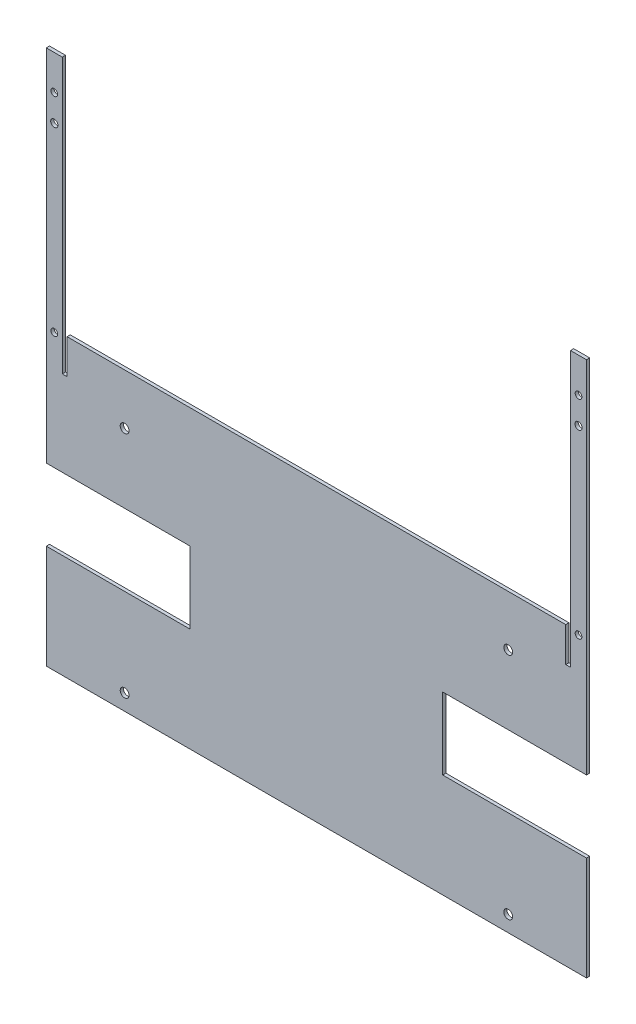
SolidWorks part; units mm, degrees
ref_plane "Plan de face" through (0, 0, 0) normal (0, 0, 1) x (1, 0, 0)
ref_plane "Plan de dessus" through (0, 0, 0) normal (0, 1, 0) x (1, 0, 0)
ref_plane "Plan de droite" through (0, 0, 0) normal (1, 0, 0) x (0, 0, -1)
sketch "Esquisse1" plane through (0, 0, 0) normal (0, 0, 1) x (1, 0, 0)
  line L1 (-169, -167.5) -> (169, -167.5)
  line L2 (-169, -167.5) -> (-169, 167.5)
  line L3 (-169, 167.5) -> (169, 167.5)
  line L4 (169, -167.5) -> (169, 167.5)
  line L5 (-169, -167.5) -> (169, 167.5) construction
  line L6 (-169, 167.5) -> (169, -167.5) construction
  point P0 (0, 0)
  dimension "D1" = 338
  dimension "D2" = 335
extrude "Boss.-Extru.1" add sketch "Esquisse1" along normal blind 2
sketch "Esquisse2" plane through (0, 0, 2) normal (0, 0, 1) x (1, 0, 0)
  line L0 (0, 0) -> (0, 137.1014) construction
  line L1 (169, 167.5) -> (-169, 167.5) construction
  line L2 (-159, 167.5) -> (159, 167.5)
  line L4 (-159, 17.5) -> (159, 17.5)
  line L5 (159, 167.5) -> (159, 17.5)
  line L6 (169, -167.5) -> (169, 167.5) construction
  line L7 (169, -102.5) -> (79, -102.5)
  line L8 (169, -102.5) -> (169, -57.5)
  line L9 (169, -57.5) -> (79, -57.5)
  line L10 (79, -102.5) -> (79, -57.5)
  line L12 (-79, -102.5) -> (-79, -57.5)
  line L13 (-169, -57.5) -> (-79, -57.5)
  line L14 (-169, -102.5) -> (-169, -57.5)
  line L15 (-169, -102.5) -> (-79, -102.5)
  line L16 (-159, 167.5) -> (-159, 17.5)
  point P6 (0, 167.5)
  point P23 (0, 17.5)
  dimension "D1" = 10
  dimension "D2" = 150
  dimension "D3" = 45
  dimension "D4" = 90
  dimension "D5" = 57.5
extrude "Enlèv. mat.-Extru.1" cut sketch "Esquisse2" against normal through all
hole_wizard "Dégagement M41" positions "Esquisse4" profile "Esquisse3" hole size "M4" standard "Ansi Metric" end condition through all
sketch "Esquisse4" plane through (0, 0, 2) normal (0, 0, 1) x (1, 0, 0)
  line L0 (164, 129.17) -> (164, 167.5)
  line L1 (169, 167.5) -> (159, 167.5) construction
  line L3 (-164, 129.17) -> (-164, 167.5)
  line L4 (-159, 167.5) -> (-169, 167.5) construction
  point P0 (164, 129.17)
  point P2 (-164, 129.17)
  dimension "D1" = 38.33
sketch "Esquisse3" plane through (164, 129.17, 2) normal (1, 0, 0) x (0, -1, 0)
  line L0 (0, 0) -> (0, 2)
  line L1 (0, 2) -> (2.25, 2)
  line L2 (2.25, 2) -> (2.25, 0)
  line L5 (2.25, 0) -> (0, 0)
  line L11 (0, -6.35) -> (0, 107.95) construction
  dimension "Diamètre du perçage jusqu'au prochain" = 4.5
  dimension "Profondeur du perçage jusqu'au prochain" = 2
sketch "Esquisse5" plane through (0, 0, 2) normal (0, 0, 1) x (1, 0, 0)
  line L0 (0, 0) -> (0, -179.3466) construction
  line L1 (156, 17.5) -> (156, -4.17)
  line L2 (-159, 17.5) -> (-156, 17.5)
  line L3 (-159, 17.5) -> (-159, -4.17)
  line L4 (-159, -4.17) -> (-156, -4.17)
  line L5 (-156, 17.5) -> (-156, -4.17)
  line L6 (159, -4.17) -> (156, -4.17)
  line L7 (159, 17.5) -> (159, -4.17)
  line L8 (159, 17.5) -> (156, 17.5)
  dimension "D1" = 21.67
  dimension "D2" = 3
extrude "Enlèv. mat.-Extru.2" cut sketch "Esquisse5" against normal through all
sketch "Esquisse6" plane through (0, 0, 2) normal (0, 0, 1) x (1, 0, 0)
  line L0 (0, 0) -> (0, -207.4805) construction
  line L1 (-164, 129.7438) -> (-164, 97.138) construction
  line L2 (-169, 141.2413) -> (-159, 141.2413) construction
  line L3 (-159, 167.5) -> (-159, -4.17) construction
  line L4 (-169, 167.5) -> (-169, -57.5) construction
  line L5 (-159, -4.17) -> (-156, -4.17) construction
  circle A0 centre (-164, 15.83) radius 2.1
  circle A1 centre (-164, 145.83) radius 2.1
  circle A3 centre (164, 15.83) radius 2.1
  circle A4 centre (164, 145.83) radius 2.1
  point P9 (-164, 141.2413)
  dimension "D1" = 4.2
  dimension "D2" = 130
  dimension "D3" = 20
extrude "Enlèv. mat.-Extru.3" cut sketch "Esquisse6" against normal through all
sketch "Esquisse7" plane through (0, 0, 2) normal (0, 0, 1) x (1, 0, 0)
  line L0 (-215.3551, -157.5) -> (250.1125, -157.5) construction
  line L1 (-236.7172, -14.17) -> (327.7633, -14.17) construction
  line L2 (-169, -167.5) -> (169, -167.5) construction
  line L3 (0, 0) -> (0, -264.1515) construction
  line L4 (-120, -14.17) -> (-120, -157.5) construction
  line L5 (120, -14.17) -> (120, -157.5) construction
  circle A0 centre (-120, -157.5) radius 2.75
  circle A1 centre (-120, -14.17) radius 2.75
  circle A2 centre (120, -14.17) radius 2.75
  circle A3 centre (120, -157.5) radius 2.75
  dimension "D3" = 5.5
  dimension "D1" = 10
  dimension "D2" = 143.33
  dimension "D4" = 120
extrude "Enlèv. mat.-Extru.4" cut sketch "Esquisse7" against normal through all
equation "\"rayon_pignon\" = 26.0313"
equation "\"largeur_robot\" = 436mm"
equation "\"largeur_chenille\"= \"RD1@Annotations\""
equation "\"espace_sous_robot\"= \"largeur_robot\" - \"largeur_chenille\" - \"largeur_chenille\""
